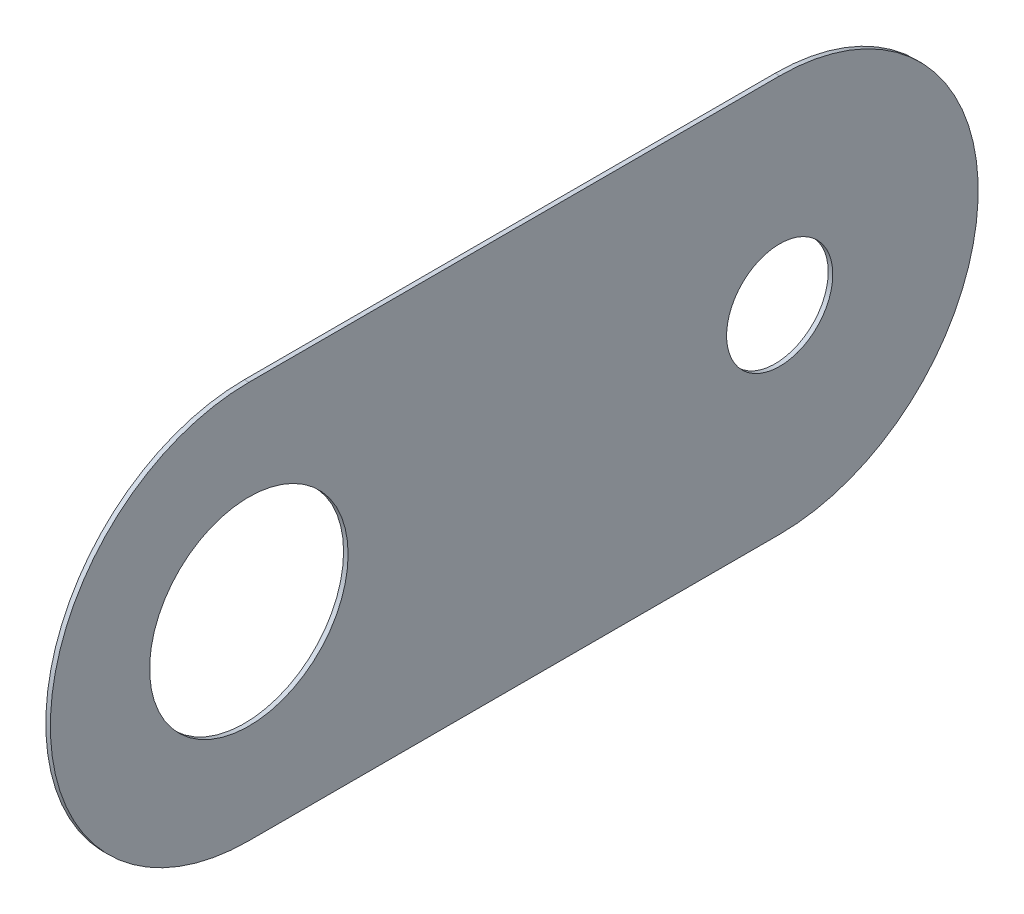
SolidWorks part; units mm, degrees
ref_plane "Front Plane" through (0, 0, 0) normal (1, 0, 0) x (0, 1, 0)
ref_plane "Top Plane" through (0, 0, 0) normal (0, 0, 1) x (0, 1, 0)
ref_plane "Right Plane" through (0, 0, 0) normal (0, 1, 0) x (-1, 0, 0)
sketch "Sketch1" plane through (0, 0, 0) normal (1, 0, 0) x (0, 1, 0)
  line L0 (0, 0) -> (0, 127)
  line L1 (94.996, 0) -> (94.996, 127)
  arc A0 (0, 127) -> (94.996, 127) centre (47.498, 127) cw
  arc A1 (0, 0) -> (94.996, 0) centre (47.498, 0) ccw
  circle A2 centre (47.498, 0) radius 12.7
  circle A3 centre (47.498, 127) radius 23.749
  point P9 (0, 71.4232)
  point P10 (58.1733, 0)
  point P11 (64.8469, 0)
  dimension "D1" = 25.4
  dimension "D2" = 47.498
  dimension "D4" = 47.498
  dimension "D3" = 127
extrude "Boss-Extrude2" add sketch "Sketch1" along normal blind 1.0871
equation "\"deflmax\"= .005"
equation "\"modulus\"= 10000000"
equation "\"Smax\"= 40000"
equation "\"force\"= 800"
equation "\"l1\"= 1"
equation "\"SF\"= 4"
equation "\"d\" = \"SF\" * ( ( \"force\" * \"l1\" * 16 ) / ( \"Smax\" * pi ) ) ^ ( 1 / 3 )"
equation "\"t2\"= \"force\" / ( \"d\" * \"Smax\" )"
equation "\"l2\"= \"modulus\" * \"d\" * \"t2\" * \"deflmax\" / \"force\""
equation "\"t4\" = .5"
equation "\"l4\"= 1.499"
equation "\"w4\" = \"l4\" * \"force\" * \"SF\" / 2 / ( \"modulus\" * \"deflmax\" * \"t4\" )"
equation "\"l5\"= \"w4\" + .9992"
equation "\"w5\" = ( ( \"force\" * \"w4\" ^ 3 * 3 ) / ( \"modulus\" * \"t4\" * \"deflmax\" * 4 ) ) ^ ( 1 / 3 )"
equation "\"l3\"= .498 + 2 * .9992 + ( \"w4\" * 2 )"
equation "\"w3\"= ( ( \"force\" * \"l3\" ^ 3 ) / ( \"modulus\" * \"t4\" * \"deflmax\" * 4 ) ) ^ ( 1 / 3 )"
equation "\"a\"= .498"
equation "\"b\"= .9992"
equation "\"l6\"= \"A6\" * \"modulus\" * \"deflmax\" / \"force\""
equation "\"t6\"= \"A6\" / ( 2 * \"R\" - \"d\" )"
equation "\"A6\" = \"SF\" * \"force\" / \"Smax\""
equation "\"R\"= \"d\""
